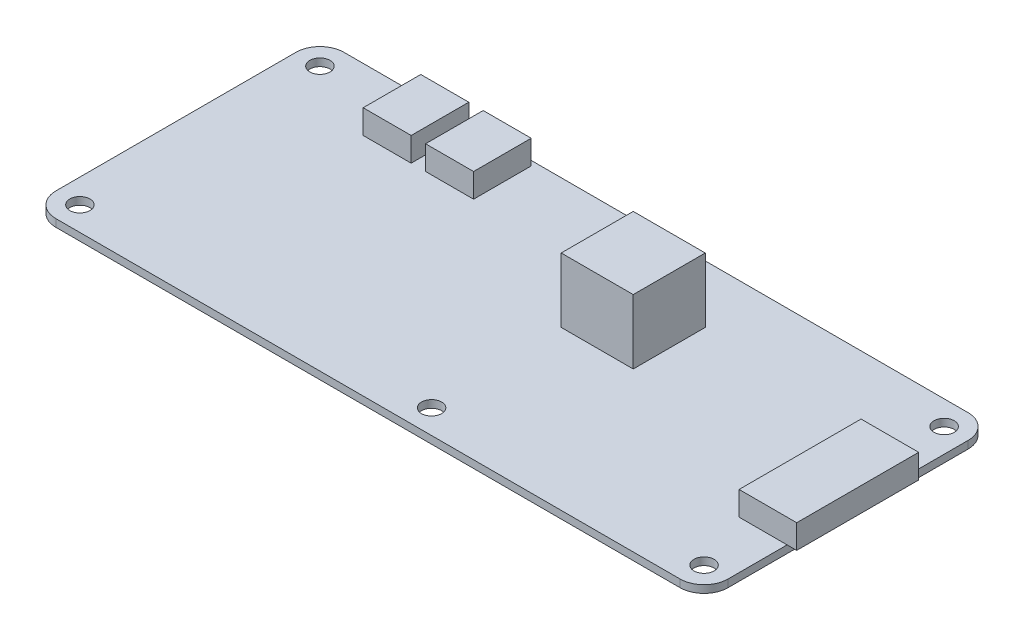
SolidWorks part; units mm, degrees
ref_plane "Front Plane" through (0, 0, 0) normal (0, 0, 1) x (1, 0, 0)
ref_plane "Top Plane" through (0, 0, 0) normal (0, 1, 0) x (1, 0, 0)
ref_plane "Right Plane" through (0, 0, 0) normal (1, 0, 0) x (0, 0, -1)
sketch "Sketch2" plane through (0, 0, 0) normal (0, 1, 0) x (1, 0, 0)
  line L0 (0, 55) -> (140, 55) construction
  line L1 (5, 0) -> (135, 0)
  line L2 (0, 5) -> (0, 55)
  line L3 (5, 60) -> (135, 60)
  line L4 (140, 5) -> (140, 55)
  line L5 (140, 5) -> (0, 5) construction
  arc A0 (0, 5) -> (5, 0) centre (5, 5) ccw
  arc A1 (140, 55) -> (135, 60) centre (135, 55) ccw
  arc A2 (135, 0) -> (140, 5) centre (135, 5) ccw
  arc A3 (5, 60) -> (0, 55) centre (5, 55) ccw
  circle A4 centre (5, 55) radius 2.1
  circle A5 centre (5, 5) radius 2.1
  circle A6 centre (135, 5) radius 2.1
  circle A7 centre (135, 55) radius 2.1
  circle A8 centre (78.25, 55) radius 2.1
  circle A9 centre (78.25, 5) radius 2.1
  point P7 (0, 0)
  point P10 (140, 60)
  point P15 (0, 60)
  dimension "D3" = 5
  dimension "D5" = 4.2
  dimension "D1" = 60
  dimension "D2" = 140
  dimension "D4" = 78.25
extrude "Boss-Extrude1" add sketch "Sketch2" along normal blind 1.5748
sketch "Sketch3" plane through (0, 1.5748, 0) normal (0, 1, 0) x (1, 0, 0)
  line L0 (140, 30) -> (142, 30) construction
  line L1 (130, 42.7) -> (142, 42.7)
  line L2 (130, 42.7) -> (130, 17.3)
  line L3 (130, 17.3) -> (142, 17.3)
  line L4 (142, 42.7) -> (142, 17.3)
  line L5 (0, 55) -> (0, 5) construction
  line L6 (140, 5) -> (140, 55) construction
  line L7 (35, 59) -> (45, 59)
  line L8 (22, 59) -> (32, 59)
  line L9 (22, 59) -> (22, 47)
  line L10 (22, 47) -> (32, 47)
  line L11 (32, 59) -> (32, 47)
  line L12 (35, 59) -> (35, 47)
  line L13 (35, 47) -> (45, 47)
  line L14 (45, 59) -> (45, 47)
  line L15 (135, 60) -> (5, 60) construction
  dimension "D1" = 2
  dimension "D2" = 25.4
  dimension "D3" = 12
  dimension "D4" = 22
  dimension "D5" = 3
  dimension "D6" = 1
  dimension "D7" = 12
  dimension "D8" = 10
extrude "Boss-Extrude2" add sketch "Sketch3" along normal blind 5 contours L4 L3 L2 L1 | L9 L8 L11 L10 | L12 L7 L14 L13
sketch "Sketch5" plane through (0, 1.5748, 0) normal (0, 1, 0) x (1, 0, 0)
  line L0 (135, 60) -> (5, 60) construction
  line L1 (77.25, 48) -> (92.25, 48)
  line L2 (77.25, 48) -> (77.25, 33)
  line L3 (77.25, 33) -> (92.25, 33)
  line L4 (92.25, 48) -> (92.25, 33)
  circle A1 centre (78.25, 55) radius 2.1 construction
  point P6 (84.2335, 35)
  dimension "D1" = 12
  dimension "D2" = 15
  dimension "D3" = 1
extrude "Boss-Extrude3" add sketch "Sketch5" along normal offset from surface (13.4252 mm away) 15 up to face at (70, 0, -30) offset beyond the face yes
